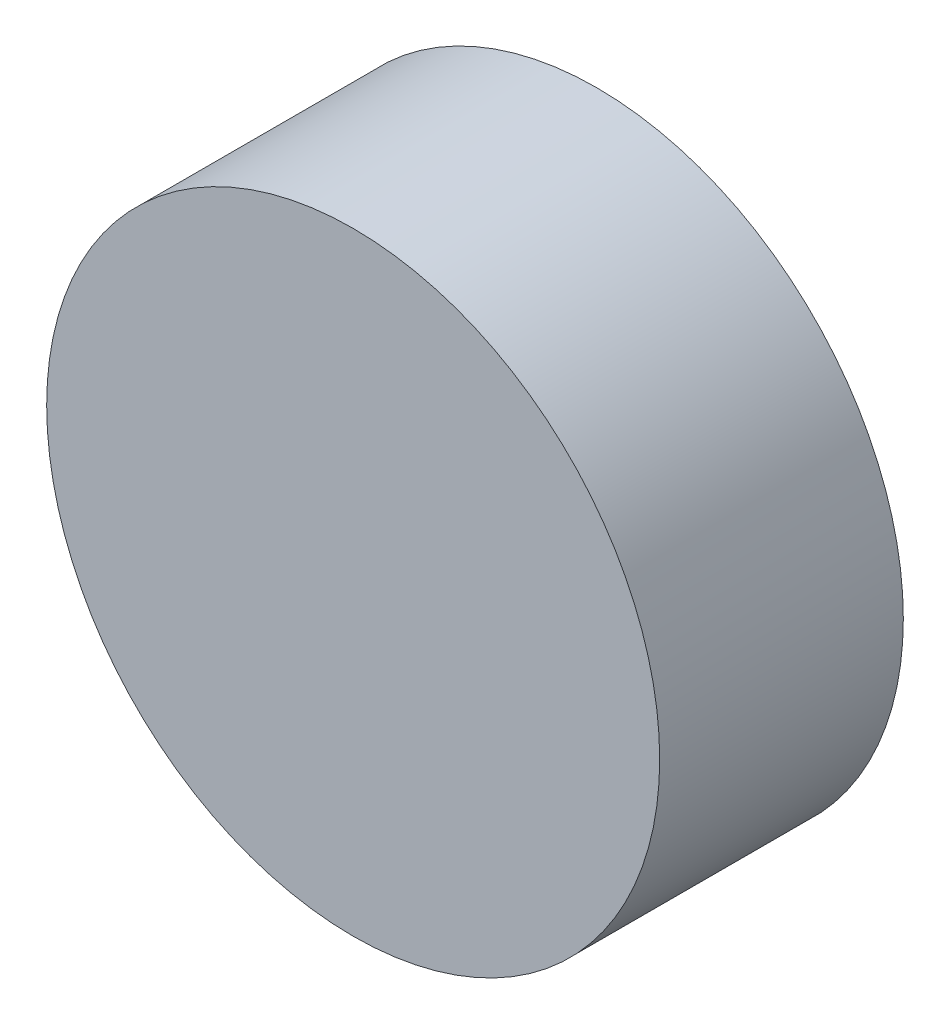
SolidWorks part; units mm, degrees
ref_plane "Front Plane" through (0, 0, 0) normal (0, 0, 1) x (1, 0, 0)
ref_plane "Top Plane" through (0, 0, 0) normal (0, 1, 0) x (1, 0, 0)
ref_plane "Right Plane" through (0, 0, 0) normal (1, 0, 0) x (0, 0, -1)
sketch "Sketch1" plane through (0, 0, 0) normal (0, 0, 1) x (1, 0, 0)
  circle A0 centre (0, 0) radius 29
  dimension "D1" = 58
extrude "Boss-Extrude1" add sketch "Sketch1" along normal blind 23.0502
sketch "Sketch2" plane through (0, 0, 0) normal (0, 0, 1) x (1, 0, 0)
  line L0 (0, 29) -> (0, -29) construction
  line L1 (-29, 0) -> (29, 0) construction
  circle A0 centre (0, 0) radius 29 construction
sketch "Sketch3" plane through (0, 0, 0) normal (0, 0, -1) x (-1, 0, 0)
  line L0 (29, 0) -> (-29, 0) construction
  point P0 (0, 0)
